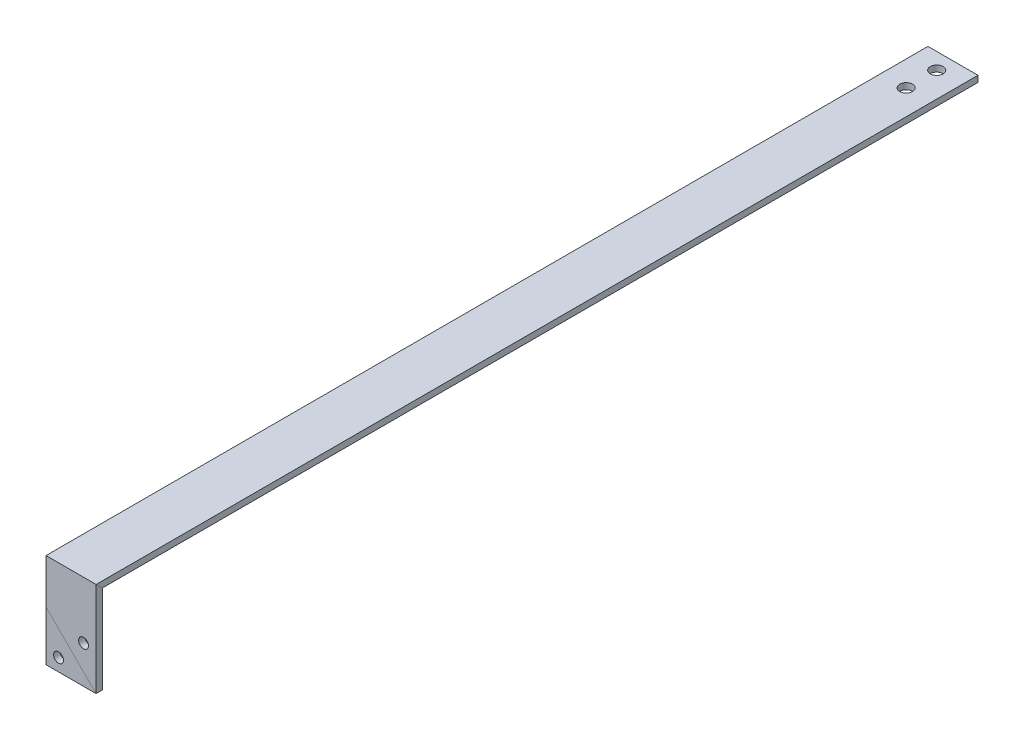
SolidWorks part; units mm, degrees
ref_plane "Alzado" through (0, 0, 0) normal (0, 0, 1) x (1, 0, 0)
ref_plane "Planta" through (0, 0, 0) normal (0, 1, 0) x (1, 0, 0)
ref_plane "Vista lateral" through (0, 0, 0) normal (1, 0, 0) x (0, 0, -1)
sketch "Croquis1" plane through (0, 0, 0) normal (0, 0, 1) x (1, 0, 0)
  line L1 (-25.4, 3.155) -> (25.4, 3.155)
  line L2 (-25.4, 3.155) -> (-25.4, -3.155)
  line L3 (-25.4, -3.155) -> (25.4, -3.155)
  line L4 (25.4, 3.155) -> (25.4, -3.155)
  line L5 (-25.4, 3.155) -> (25.4, -3.155) construction
  line L6 (-25.4, -3.155) -> (25.4, 3.155) construction
  point P0 (0, 0)
  dimension "D1" = 50.8
  dimension "D2" = 6.31
sketch3d "Croquis3D1"
  line L0 (0, 0, 0) -> (0, 0, 891.73)
  line L1 (0, 0, 891.73) -> (0, -67.38, 891.73)
  line L2 (0, -67.38, 891.73) -> (-84.6, -67.38, 891.73)
  dimension "D1" = 891.73
  dimension "D2" = 67.38
  dimension "D3" = 84.6
sweep "Barrer1" add profiles "Croquis1" path "Croquis3D1"
sketch "Croquis2" plane through (0, 3.155, 0) normal (0, 1, 0) x (1, 0, 0)
  line L0 (0, 0) -> (0, -16.5) construction
  line L1 (0, -16.5) -> (0, -47.5) construction
  circle A0 centre (0, -16.5) radius 6.5
  circle A1 centre (0, -47.5) radius 6.5
  dimension "D1" = 13
  dimension "D2" = 13
extrude "Cortar-Extruir1" cut sketch "Croquis2" against normal blind 10
sketch "Croquis3" plane through (0, 0, 846.7461) normal (0, 0, -1) x (-1, 0, 0)
  line L0 (60, -67.3787) -> (63.1123, -64.2664) construction
sketch "Croquis5" plane through (0, 0, 888.575) normal (0, 0, -1) x (-1, 0, 0)
  line L0 (84.6, -92.78) -> (84.6, -41.98) construction
  line L1 (84.6, -41.98) -> (84.6, -67.38) construction
  line L2 (84.6, -67.38) -> (66.5, -67.38) construction
  line L3 (-25.4, -92.78) -> (84.6, -92.78) construction
  circle A0 centre (60, -67.38) radius 6.5
  dimension "D2" = 13
  dimension "D4" = 25.4
  dimension "D1" = 24.6
extrude "Cortar-Extruir4" cut sketch "Croquis5" against normal blind 10
sketch "Croquis7" plane through (0, 0, 888.575) normal (0, 0, -1) x (-1, 0, 0)
  line L0 (25.4, -41.98) -> (25.4, -92.78)
  line L1 (-25.4, -92.78) -> (84.6, -92.78) construction
  line L2 (25.4, -92.78) -> (84.6, -92.78)
  line L3 (84.6, -92.78) -> (84.6, -41.98)
  line L4 (25.4, -41.98) -> (84.6, -41.98)
extrude "Cortar-Extruir5" cut sketch "Croquis7" against normal blind 6.31
sketch "Croquis8" plane through (0, 0, 888.575) normal (0, 0, -1) x (-1, 0, 0)
  line L0 (25.4, -92.78) -> (25.4, -41.98) construction
  line L1 (25.4, -41.98) -> (-25.4, -41.98) construction
  line L2 (-25.4, -3.155) -> (-25.4, -92.78) construction
  line L3 (-25.4, -41.98) -> (25.4, -92.78) construction
  line L4 (25.4, -92.78) -> (0, -67.38) construction
  line L5 (0, -67.38) -> (25.4, -67.38) construction
  line L6 (25.4, -67.38) -> (0, -67.38) construction
  line L7 (0, -67.38) -> (25.4, -92.78) construction
  line L8 (25.4, -92.78) -> (12.7, -80.08) construction
  line L9 (0, -67.38) -> (-25.4, -41.98) construction
  line L10 (-25.4, -41.98) -> (-12.7, -54.68) construction
  circle A0 centre (-12.7, -54.68) radius 5
  circle A1 centre (12.7, -80.08) radius 5
  dimension "D1" = 10
  dimension "D2" = 10
extrude "Cortar-Extruir6" cut sketch "Croquis8" against normal blind 10
